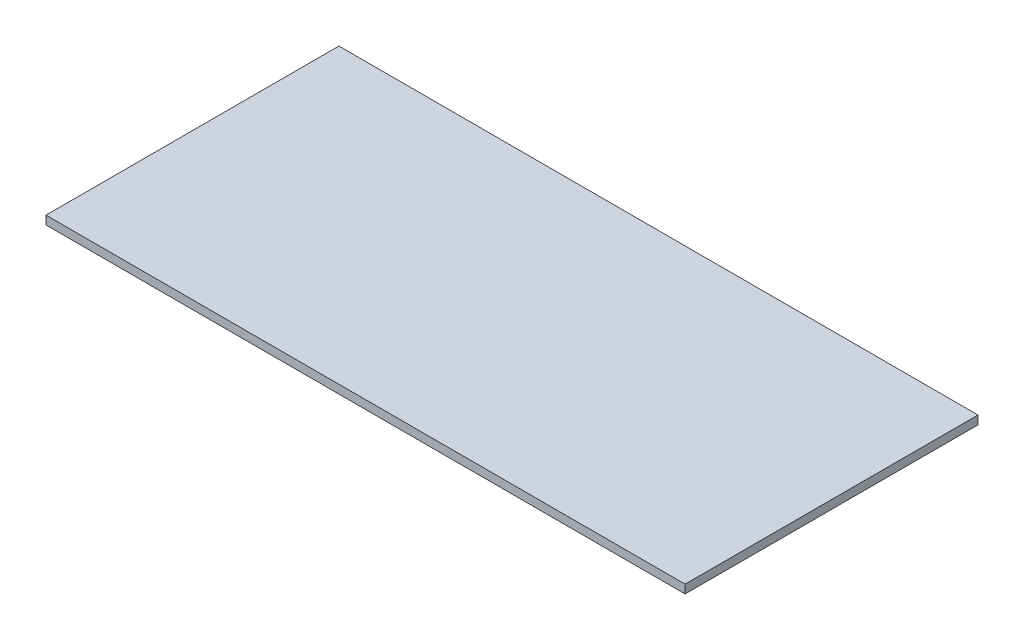
SolidWorks part; units mm, degrees
ref_plane "Front Plane" through (0, 0, 0) normal (0, 0, 1) x (1, 0, 0)
ref_plane "Top Plane" through (0, 0, 0) normal (0, 1, 0) x (1, 0, 0)
ref_plane "Right Plane" through (0, 0, 0) normal (1, 0, 0) x (0, 0, -1)
sketch "Sketch1" plane through (0, 0, 0) normal (0, 1, 0) x (1, 0, 0)
  line L1 (-60, -27.5) -> (60, -27.5)
  line L2 (-60, -27.5) -> (-60, 27.5)
  line L3 (-60, 27.5) -> (60, 27.5)
  line L4 (60, -27.5) -> (60, 27.5)
extrude "Plate_Extrude" add sketch "Sketch1" along normal blind 1.6
equation "\"ValveDiameter\" = 50mm"
equation "\"MotorGearTeeth\" = 40"
equation "\"OutputGearTeeth\" = 80"
equation "\"GearModule\" = 1.5mm"
equation "\"PressureAngle\" = 20deg"
equation "\"GearCenterDistance\" = 90mm"
equation "\"GearWidth\" = 18mm"
equation "\"OutputShaftDiameter\" = 20mm"
equation "\"BearingOD\" = 47mm"
equation "\"BearingWidth\" = 14mm"
equation "\"PlateThickness\" = 6mm"
equation "\"ValveRotation\" = 90deg"
